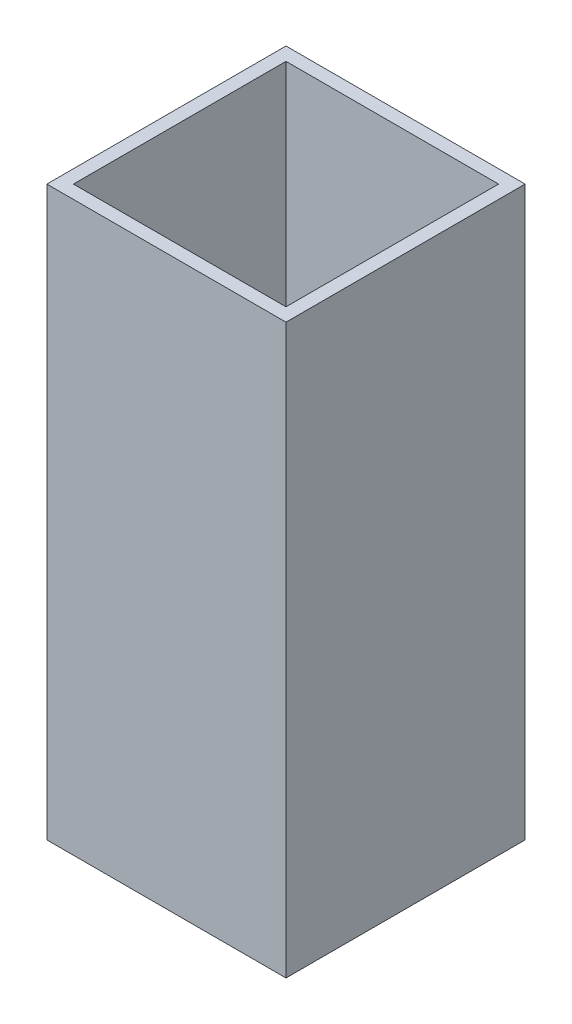
SolidWorks part; units mm, degrees
ref_plane "Front Plane" through (0, 0, 0) normal (0, 0, 1) x (1, 0, 0)
ref_plane "Top Plane" through (0, 0, 0) normal (0, 1, 0) x (1, 0, 0)
ref_plane "Right Plane" through (0, 0, 0) normal (1, 0, 0) x (0, 0, -1)
sketch "Sketch1" plane through (0, 0, 0) normal (0, 1, 0) x (1, 0, 0)
  line L1 (-77.0445, 48.0093) -> (-45.0445, 48.0093)
  line L2 (-77.0445, 48.0093) -> (-77.0445, 16.0093)
  line L3 (-77.0445, 16.0093) -> (-45.0445, 16.0093)
  line L4 (-45.0445, 48.0093) -> (-45.0445, 16.0093)
  line L5 (-79.0445, 50.0093) -> (-43.0445, 50.0093)
  line L6 (-79.0445, 50.0093) -> (-79.0445, 14.0093)
  line L7 (-79.0445, 14.0093) -> (-43.0445, 14.0093)
  line L8 (-43.0445, 50.0093) -> (-43.0445, 14.0093)
  dimension "D1" = 32
  dimension "D2" = 32
  dimension "D3" = 2
  dimension "D4" = 2
  dimension "D5" = 2
  dimension "D6" = 2
extrude "Boss-Extrude1" add sketch "Sketch1" along normal blind 10
sketch "Sketch2" plane through (0, 0, 0) normal (0, -1, 0) x (1, 0, 0)
  line L1 (-43.0445, -14.0093) -> (-79.0445, -14.0093)
  line L2 (-43.0445, -14.0093) -> (-43.0445, -50.0093)
  line L3 (-43.0445, -50.0093) -> (-79.0445, -50.0093)
  line L4 (-79.0445, -14.0093) -> (-79.0445, -50.0093)
  line L5 (-75.0445, -18.0093) -> (-47.0445, -18.0093)
  line L6 (-75.0445, -18.0093) -> (-75.0445, -46.0093)
  line L7 (-75.0445, -46.0093) -> (-47.0445, -46.0093)
  line L8 (-47.0445, -18.0093) -> (-47.0445, -46.0093)
  dimension "D1" = 4
  dimension "D2" = 4
  dimension "D3" = 4
  dimension "D4" = 4
sketch "Sketch5" plane through (0, 10, 0) normal (0, 1, 0) x (1, 0, 0)
  line L1 (-79.0445, 50.0093) -> (-43.0445, 50.0093)
  line L2 (-79.0445, 50.0093) -> (-79.0445, 14.0093)
  line L3 (-79.0445, 14.0093) -> (-43.0445, 14.0093)
  line L4 (-43.0445, 50.0093) -> (-43.0445, 14.0093)
  line L10 (-77.0445, 48.0093) -> (-77.0445, 16.0093) construction
  line L11 (-43.0445, 14.0093) -> (-79.0445, 14.0093)
  line L12 (-43.0445, 14.0093) -> (-43.0445, 50.0093)
  line L13 (-43.0445, 50.0093) -> (-79.0445, 50.0093)
  line L14 (-79.0445, 14.0093) -> (-79.0445, 50.0093)
  line L15 (-77.0445, 16.0093) -> (-45.0445, 16.0093) construction
  line L16 (-45.0445, 48.0093) -> (-77.0445, 48.0093) construction
  line M5 (-45.0445, 16.0093) -> (-77.0445, 16.0093)
  line M6 (-77.0445, 16.0093) -> (-77.0445, 48.0093)
  line M7 (-77.0445, 48.0093) -> (-45.0445, 48.0093)
  line M8 (-45.0445, 48.0093) -> (-45.0445, 16.0093)
  dimension "D3" = 2
  dimension "D4" = 2
  dimension "D1" = 2
  dimension "D2" = 2
extrude "Boss-Extrude5" add sketch "Sketch5" along normal blind 63.5 contours L14 L11 L12 L13 M8 M5 M6 M7
extrude "Boss-Extrude9" add sketch "Sketch2" along normal blind 2
sketch "Sketch9" plane through (0, -2, 0) normal (0, -1, 0) x (1, 0, 0)
  line L1 (-79.0445, -14.0093) -> (-43.0445, -14.0093)
  line L2 (-79.0445, -14.0093) -> (-79.0445, -50.0093)
  line L3 (-79.0445, -50.0093) -> (-43.0445, -50.0093)
  line L4 (-43.0445, -14.0093) -> (-43.0445, -50.0093)
  line L5 (-77.0445, -16.0093) -> (-45.0445, -16.0093)
  line L6 (-77.0445, -16.0093) -> (-77.0445, -48.0093)
  line L7 (-77.0445, -48.0093) -> (-45.0445, -48.0093)
  line L8 (-45.0445, -16.0093) -> (-45.0445, -48.0093)
  dimension "D3" = 2
  dimension "D4" = 2
  dimension "D1" = 2
  dimension "D2" = 2
extrude "Boss-Extrude11" add sketch "Sketch9" along normal blind 10
equation "\"tolerance\"= 2"
equation "\"length\"= 30"
equation "\"D1@Sketch1\"=\"length\"+\"tolerance\""
equation "\"D2@Sketch1\"=\"length\"+\"tolerance\""
equation "\"protrusion_thickness\" = 2"
equation "\"D3@Sketch1\"=\"protrusion_thickness\""
equation "\"D4@Sketch1\"=\"protrusion_thickness\""
equation "\"D5@Sketch1\"=\"protrusion_thickness\""
equation "\"locking protrusion thickness\"=2"
equation "\"D1@Sketch2\"=\"protrusion_thickness\"+\"locking protrusion thickness\""
equation "\"D2@Sketch2\"=\"D1@Sketch2\""
equation "\"D3@Sketch2\"=\"D1@Sketch2\""
equation "\"D4@Sketch2\"=\"D1@Sketch2\""
equation "\"D1@Boss-Extrude1\"=10"
equation "\"D1@Sketch5\"=\"locking protrusion thickness\""
equation "\"D2@Sketch5\"=\"locking protrusion thickness\""
equation "\"D3@Sketch5\"=\"locking protrusion thickness\""
equation "\"D4@Sketch5\"=\"locking protrusion thickness\""
equation "\"D1@Sketch9\"=\"locking protrusion thickness\""
equation "\"D2@Sketch9\"=\"locking protrusion thickness\""
equation "\"D3@Sketch9\"=\"locking protrusion thickness\""
equation "\"D4@Sketch9\"=\"locking protrusion thickness\""
equation "\"D1@Boss-Extrude5\"=2.5*25.4"
